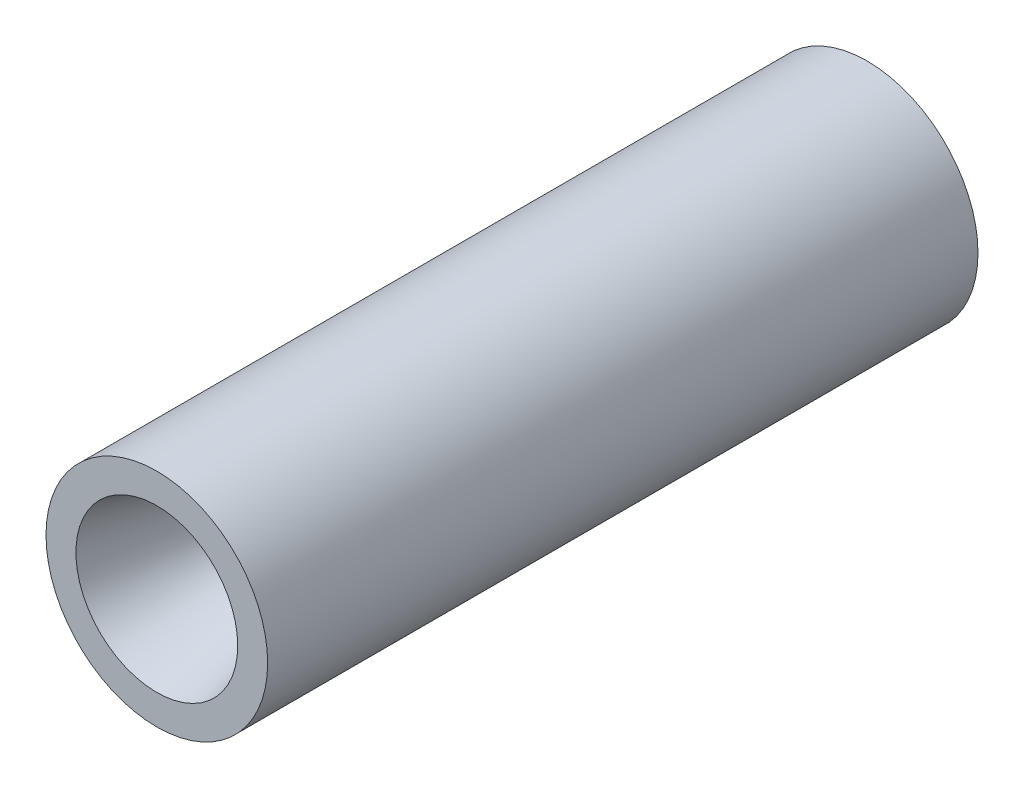
SolidWorks part; units mm, degrees
material "ABS"
ref_plane "Front Plane" through (0, 0, 0) normal (0, 0, 1) x (1, 0, 0)
ref_plane "Top Plane" through (0, 0, 0) normal (0, 1, 0) x (1, 0, 0)
ref_plane "Right Plane" through (0, 0, 0) normal (1, 0, 0) x (0, 0, -1)
sketch "Sketch1" plane through (0, 0, 0) normal (0, 0, 1) x (1, 0, 0)
  circle A0 centre (0, 0) radius 25.4
extrude "Boss-Extrude1" add sketch "Sketch1" along normal mid plane 162.814
sketch "Sketch2" plane through (0, 0, 81.407) normal (0, 0, 1) x (1, 0, 0)
  circle A0 centre (0, 0) radius 3.81
extrude "Cut-Extrude2" cut sketch "Sketch2" against normal through all contours A0
ref_axis "Axis1" through (0, 0, -89.5477) along (0, 0, 1)
sketch "Sketch6" plane through (0, 0, 0) normal (1, 0, 0) x (0, 0, -1)
  line L0 (-12.2073, 0) -> (-81.407, 18.542)
  line L3 (89.5477, 0) -> (-89.5477, 0) construction
  line L4 (-81.407, 25.4) -> (-81.407, -25.4) construction
  line L5 (-81.407, 18.542) -> (-81.407, 0)
  line L6 (-81.407, 0) -> (-12.2073, 0)
  dimension "D1" = 15
  dimension "D2" = 18.542
revolve "Cut-Revolve1" cut sketch "Sketch6" angle 360 about axis through (0, 0, -89.5477) along (0, 0, 1)
